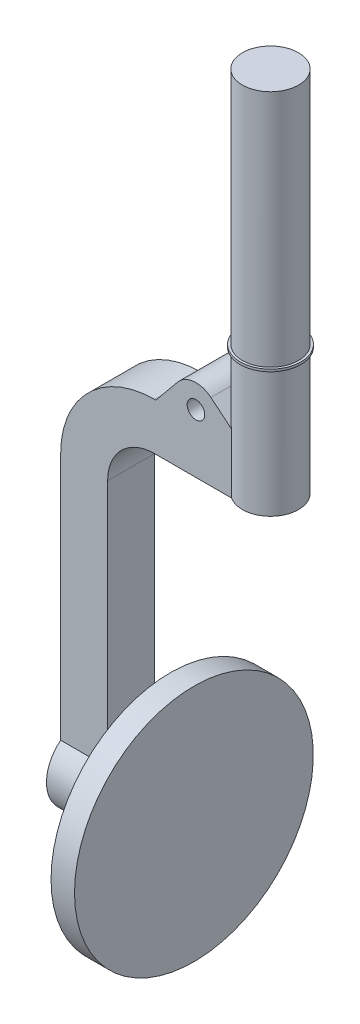
SolidWorks part; units mm, degrees
material "Choose your Material"
ref_plane "Front Plane" through (0, 0, 0) normal (0, 0, 1) x (1, 0, 0)
ref_plane "Top Plane" through (0, 0, 0) normal (0, 1, 0) x (1, 0, 0)
ref_plane "Right Plane" through (0, 0, 0) normal (1, 0, 0) x (0, 0, -1)
sketch "Sketch1" plane through (0, 0, 0) normal (0, 0, 1) x (1, 0, 0)
  line L0 (-123.19, -150.1775) -> (-123.19, 150.1775)
  line L1 (-72.39, 200.9775) -> (27.6225, 200.9775)
  line L2 (-173.99, -150.1775) -> (-173.99, 150.1775)
  line L3 (-72.39, 251.7775) -> (-71.0661, 251.7775)
  line L4 (-173.99, -150.1775) -> (-123.19, -150.1775)
  line L5 (27.6225, 200.9775) -> (27.6225, 251.7775)
  line L6 (-123.19, -150.1775) -> (-123.19, 200.9775) construction
  line L7 (-123.19, 200.9775) -> (27.6225, 200.9775) construction
  line L8 (-173.99, -150.1775) -> (-173.99, 251.7775) construction
  line L9 (-173.99, 251.7775) -> (27.6225, 251.7775) construction
  line L10 (-11.4431, 284.0578) -> (27.6225, 251.7775)
  line L11 (-47.2028, 280.6569) -> (-71.0661, 251.7775)
  line L12 (27.6225, -508.508) -> (27.6225, 208.153) construction
  arc A0 (-123.19, 150.1775) -> (-72.39, 200.9775) centre (-72.39, 150.1775) cw
  arc A1 (-173.99, 150.1775) -> (-72.39, 251.7775) centre (-72.39, 150.1775) cw
  arc A2 (-11.4431, 284.0578) -> (-47.2028, 280.6569) centre (-27.6225, 264.4775) ccw
  circle A3 centre (-27.6225, 264.4775) radius 9.525
  point P3 (-123.19, 0)
  point P12 (-123.19, 200.9775)
  dimension "D5" = 101.6
  dimension "D7" = 50.8
  dimension "D9" = 19.05
  dimension "D1" = 123.19
  dimension "D3" = 351.155
  dimension "D6" = 55.245
  dimension "D8" = 12.7
  dimension "D4" = 50.8
extrude "Boss-Extrude1" add sketch "Sketch1" along normal mid plane 50.8
sketch "Sketch2" plane through (0, -150.1775, 0) normal (0, -1, 0) x (1, 0, 0)
  line L0 (-173.99, 0) -> (-123.19, 0)
  line L1 (-173.99, 25.4) -> (-173.99, -25.4) construction
  line L2 (-123.19, 25.4) -> (-123.19, -25.4) construction
  line L3 (-173.99, 0) -> (-173.99, 40.7194)
  line L4 (-173.99, 40.7194) -> (-123.19, 40.7194)
  line L5 (-123.19, 40.7194) -> (-123.19, 25.4)
  line L6 (-123.19, 25.4) -> (-80.645, 25.4)
  line L7 (-80.645, 25.4) -> (-80.645, 129.159)
  line L8 (-80.645, 129.159) -> (-55.245, 129.159)
  line L9 (-55.245, 129.159) -> (-55.245, 0)
  line L10 (-55.245, 0) -> (-123.19, 0)
  line L11 (-123.19, 25.4) -> (-123.19, -25.4) construction
  dimension "D1" = 40.7194
  dimension "D2" = 129.159
  dimension "D3" = 25.4
  dimension "D4" = 25.4
  dimension "D5" = 67.945
revolve "Revolve1" add sketch "Sketch2" angle 360 about L0
sketch "Sketch3" plane through (0, 200.9775, 0) normal (0, -1, 0) x (1, 0, 0)
  line L0 (27.6225, 25.4) -> (27.6225, -25.4) construction
  circle A0 centre (27.6225, 0) radius 30.353
  dimension "D1" = 60.706
extrude "Boss-Extrude2" add sketch "Sketch3" against normal blind 397.764
ref_plane "Plane1" through (0, 289.8775, 0) normal (0, 1, 0) x (1, 0, 0)
ref_plane "Plane2" through (0, 340.6775, 0) normal (0, 1, 0) x (1, 0, 0)
sketch "Sketch4" plane through (0, 340.6775, 0) normal (0, 1, 0) x (1, 0, 0)
  circle A0 centre (27.6225, 0) radius 32.893
  arc A1 (11.0049, -25.4) -> (11.0049, 25.4) centre (27.6225, 0) ccw construction
  dimension "D1" = 2.54
extrude "Boss-Extrude3" add sketch "Sketch4" against normal blind 2.54
equation "\"wheelwidth\"=8.7"
equation "\"D1@Sketch1\"=\"wheelwidth\"/2 + 0.5"
equation "\"diameter\"= 25.65"
equation "\"D1@Boss-Extrude1\"=2"
equation "\"D1@Sketch2\"=\"diameter\"/16"
equation "\"OleoDia\"=2.39"
equation "\"D1@Sketch3\"=\"OleoDia\""
equation "\"OleoStroke\"=8.66"
equation "\"D1@Boss-Extrude2\"=\"OleoStroke\"+7"
equation "\"D2@Sketch2\"=(\"diameter\"/2-\"wheelwidth\"/2)*0.6"
equation "\"D5@Sketch2\"=\"wheelwidth\"/4+0.5"
equation "\"D6@Sketch1\"=\"wheelwidth\"/4"
